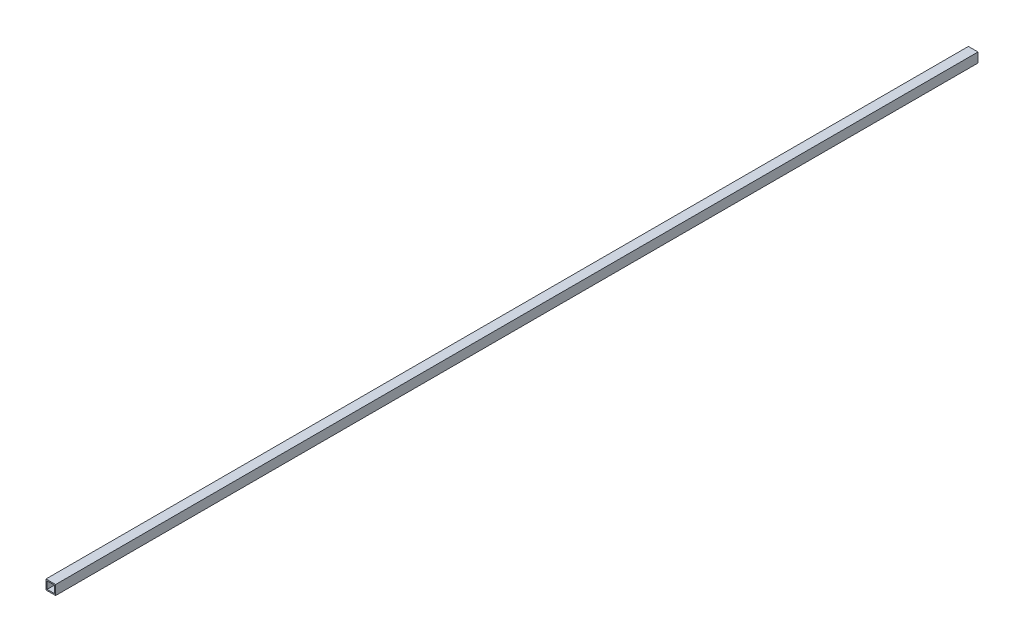
SolidWorks part; units mm, degrees
material "Plain Carbon Steel"
ref_plane "Front Plane" through (0, 0, 0) normal (0, 0, 1) x (1, 0, 0)
ref_plane "Top Plane" through (0, 0, 0) normal (0, 1, 0) x (1, 0, 0)
ref_plane "Right Plane" through (0, 0, 0) normal (1, 0, 0) x (0, 0, -1)
sketch "Sketch1" plane through (0, 0, 0) normal (0, 0, 1) x (1, 0, 0)
  line L0 (3.0378, 12.7) -> (0, 12.7) construction
  line L1 (0, 0) -> (25.4, 0)
  line L2 (0, 0) -> (0, 25.4)
  line L3 (0, 25.4) -> (25.4, 25.4)
  line L4 (25.4, 0) -> (25.4, 25.4)
  line L5 (3.0378, 3.0378) -> (22.3622, 3.0378)
  line L6 (3.0378, 3.0378) -> (3.0378, 22.3622)
  line L7 (3.0378, 22.3622) -> (22.3622, 22.3622)
  line L8 (22.3622, 3.0378) -> (22.3622, 22.3622)
  line L9 (12.7, 3.0378) -> (12.7, 0) construction
  line L10 (12.7, 22.3622) -> (12.7, 25.4) construction
  line L11 (25.4, 12.7) -> (22.3622, 12.7) construction
  dimension "D1" = 25.4
  dimension "D2" = 25.4
  dimension "D3" = 3.0378
extrude "Boss-Extrude1" add sketch "Sketch1" along normal blind 2438.4
